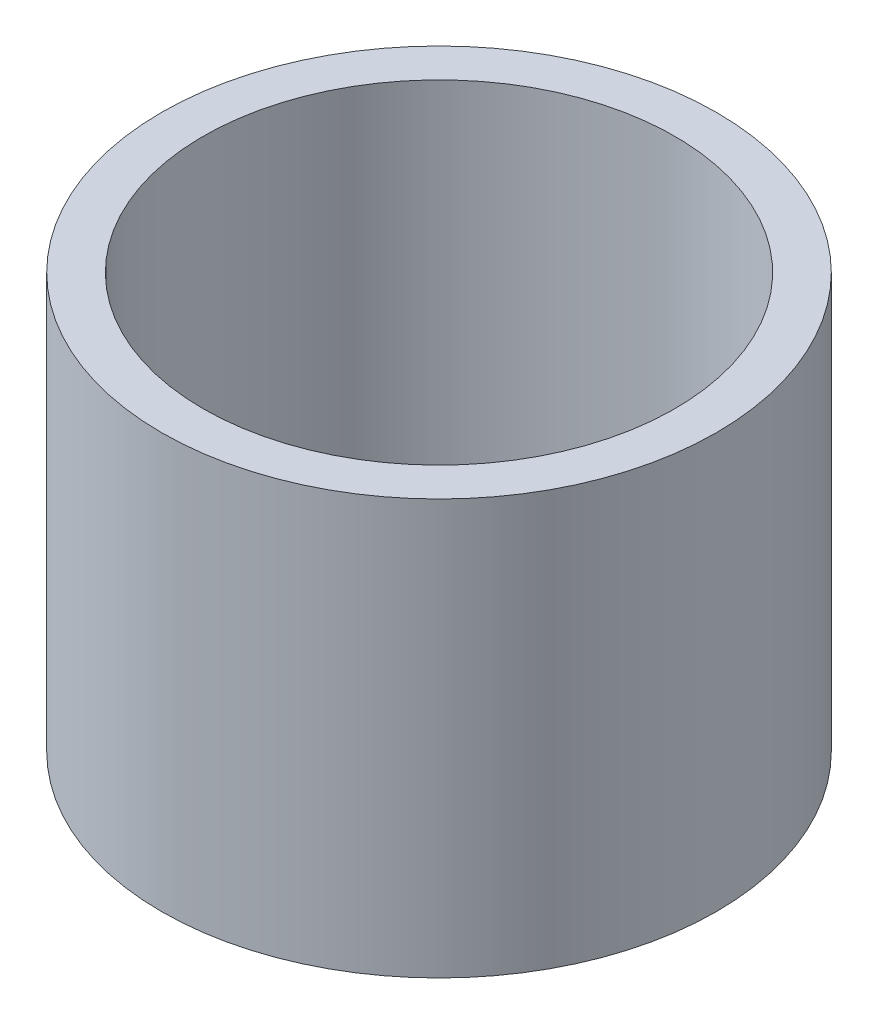
SolidWorks part; units mm, degrees
ref_plane "前视基准面" through (0, 0, 0) normal (0, 0, 1) x (1, 0, 0)
ref_plane "上视基准面" through (0, 0, 0) normal (0, 1, 0) x (1, 0, 0)
ref_plane "右视基准面" through (0, 0, 0) normal (1, 0, 0) x (0, 0, -1)
sketch "草图1" plane through (0, 0, 0) normal (0, 1, 0) x (1, 0, 0)
  circle A0 centre (0, 0) radius 21.4
  dimension "D1" = 42.8
extrude "凸台-拉伸1" add sketch "草图1" along normal blind 32
sketch "草图2" plane through (0, 32, 0) normal (0, 1, 0) x (1, 0, 0)
  circle A0 centre (0, 0) radius 18.2
  circle A1 centre (0, 0) radius 21.4 construction
  dimension "D1" = 3.2
extrude "切除-拉伸1" cut sketch "草图2" against normal through all
